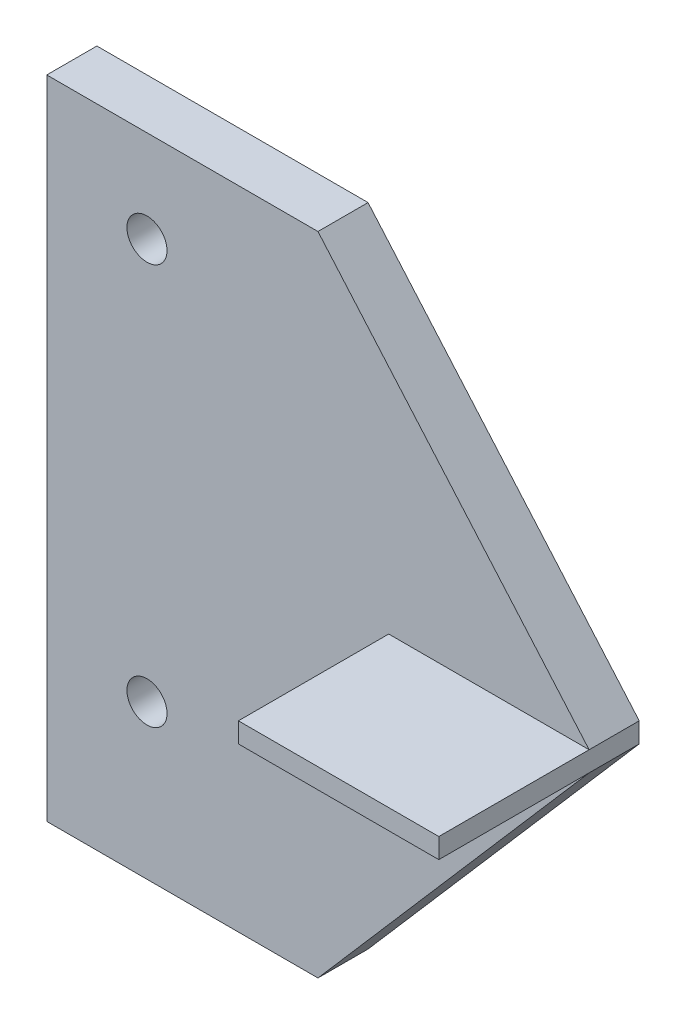
SolidWorks part; units mm, degrees
ref_plane "Front Plane" through (0, 0, 0) normal (0, 0, 1) x (1, 0, 0)
ref_plane "Top Plane" through (0, 0, 0) normal (0, 1, 0) x (1, 0, 0)
ref_plane "Right Plane" through (0, 0, 0) normal (1, 0, 0) x (0, 0, -1)
sketch "Sketch1" plane through (0, 0, 0) normal (0, 0, 1) x (1, 0, 0)
  line L1 (-320.2, -170.8132) -> (-266.0753, -170.8132)
  line L2 (-320.2, -170.8132) -> (-320.2, -235.3329)
  line L3 (-320.2, -235.3329) -> (-266.0753, -235.3329)
  line L5 (-320.2, -170.8132) -> (-266.0753, -235.3329) construction
  line L6 (-320.2, -235.3329) -> (-266.0753, -170.8132) construction
  line L9 (-296.0753, -125.75) -> (-296.0753, -274.25) construction
  line L10 (-296.0753, -274.25) -> (-271.0753, -125.75) construction
  line L11 (-271.0753, -125.75) -> (-271.0753, -274.25) construction
  line L12 (-271.0753, -330) -> (-271.0753, -274.25) construction
  line L13 (-271.0753, -274.25) -> (-261.0753, -274.25) construction
  line L14 (-271.0753, -274.25) -> (-296.0753, -274.25) construction
  line L15 (-266.0753, -170.8132) -> (-266.0753, -235.3329)
  circle A0 centre (-310.2, -180) radius 2
  circle A1 centre (-310.2, -220) radius 2
  point P4 (-293.1376, -203.073)
  dimension "D1" = 4
  dimension "D2" = 10
  dimension "D3" = 5
extrude "Boss-Extrude1" add sketch "Sketch1" along normal blind 5
sketch "Sketch2" plane through (0, -125.75, 0) normal (0, -1, 0) x (1, 0, 0)
  circle A0 centre (-283.5753, 11.6) radius 4.3
  circle A1 centre (-283.5753, 11.6) radius 7
  dimension "D1" = 14
sketch "Sketch7" plane through (-266.0753, 0, 0) normal (1, 0, 0) x (0, 0, -1)
  line L0 (0, -235.3329) -> (0, -170.8132) construction
  line L1 (0, -204.073) -> (-20, -204.073)
  line L2 (0, -204.073) -> (0, -202.073)
  line L3 (0, -202.073) -> (-20, -202.073)
  line L4 (-20, -204.073) -> (-20, -202.073)
  line L5 (0, -204.073) -> (-20, -202.073) construction
  line L6 (0, -202.073) -> (-20, -204.073) construction
  line L7 (-5, -235.3329) -> (-5, -170.8132) construction
  point P4 (-10, -203.073)
  point P11 (-5, -203.073)
  point P12 (-5, -203.073)
  point P13 (0, 0)
  point P14 (0, 0)
  dimension "D1" = 20
  dimension "D2" = 2
extrude "Boss-Extrude4" add sketch "Sketch7" against normal blind 20
sketch "Sketch8" plane through (0, 0, 5) normal (0, 0, 1) x (1, 0, 0)
  line L0 (-293.1376, -235.3329) -> (-266.0753, -204.073)
  line L1 (-320.2, -235.3329) -> (-266.0753, -235.3329) construction
  line L2 (-266.0753, -204.073) -> (-266.0753, -202.073)
  line L3 (-266.0753, -202.073) -> (-293.1376, -170.8132)
  line L4 (-266.0753, -170.8132) -> (-320.2, -170.8132) construction
  line L5 (-293.1376, -170.8132) -> (-266.0753, -170.8132)
  line L6 (-266.0753, -170.8132) -> (-266.0753, -235.3329)
  line L7 (-266.0753, -235.3329) -> (-266.0753, -204.073) construction
  line L8 (-266.0753, -235.3329) -> (-293.1376, -235.3329)
  line M4 (-266.0753, -202.073) -> (-266.0753, -170.8132)
  line M5 (-266.0753, -170.8132) -> (-320.2, -170.8132)
  line M7 (-320.2, -235.3329) -> (-266.0753, -235.3329)
  line M8 (-266.0753, -235.3329) -> (-266.0753, -204.073)
extrude "Cut-Extrude4" cut sketch "Sketch8" against normal blind 7 contours L0 M7 M8 | L3 M4 M5
